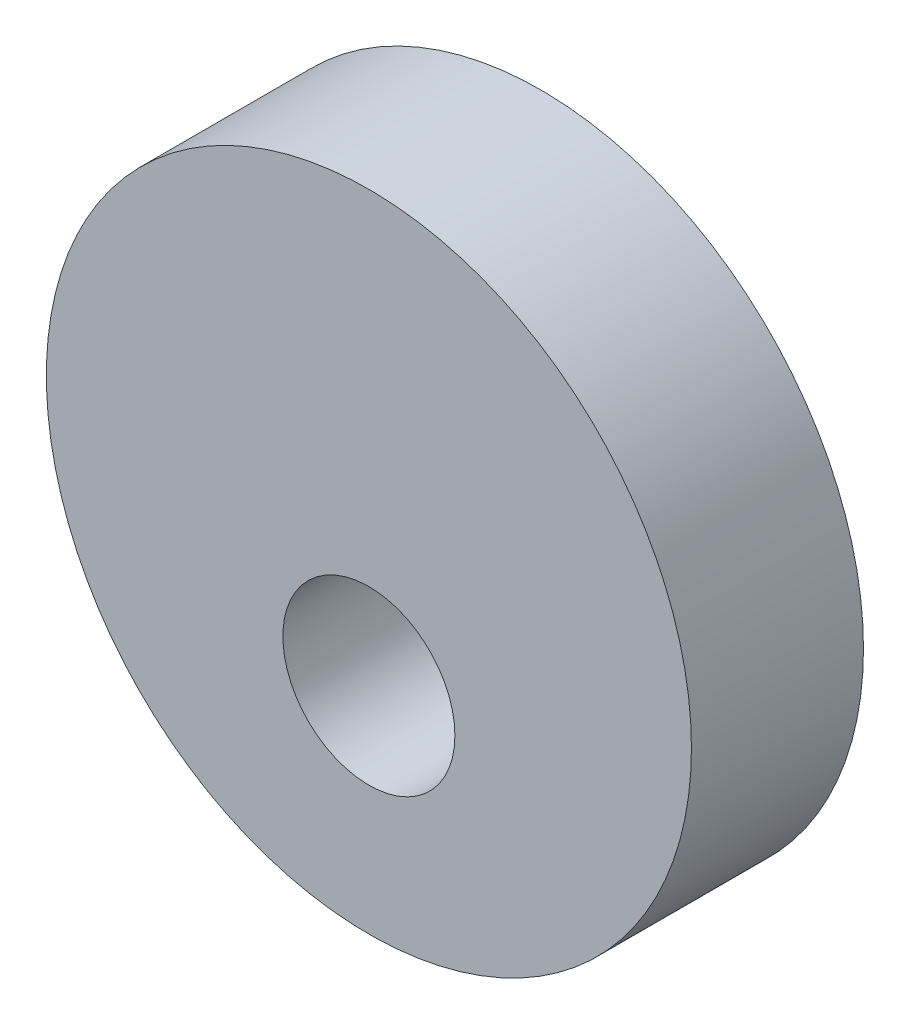
SolidWorks part; units mm, degrees
ref_plane "Front Plane" through (0, 0, 0) normal (0, 0, 1) x (1, 0, 0)
ref_plane "Top Plane" through (0, 0, 0) normal (0, 1, 0) x (1, 0, 0)
ref_plane "Right Plane" through (0, 0, 0) normal (1, 0, 0) x (0, 0, -1)
sketch "Sketch1" plane through (0, 0, 0) normal (0, 0, 1) x (1, 0, 0)
  circle A0 centre (0, 0) radius 15
extrude "Boss-Extrude1" add sketch "Sketch1" along normal blind 8
sketch "Sketch2" plane through (0, 0, 8) normal (0, 0, 1) x (1, 0, 0)
  circle A0 centre (0, -5) radius 4
  dimension "D1" = 5
extrude "Cut-Extrude1" cut sketch "Sketch2" against normal blind 10
